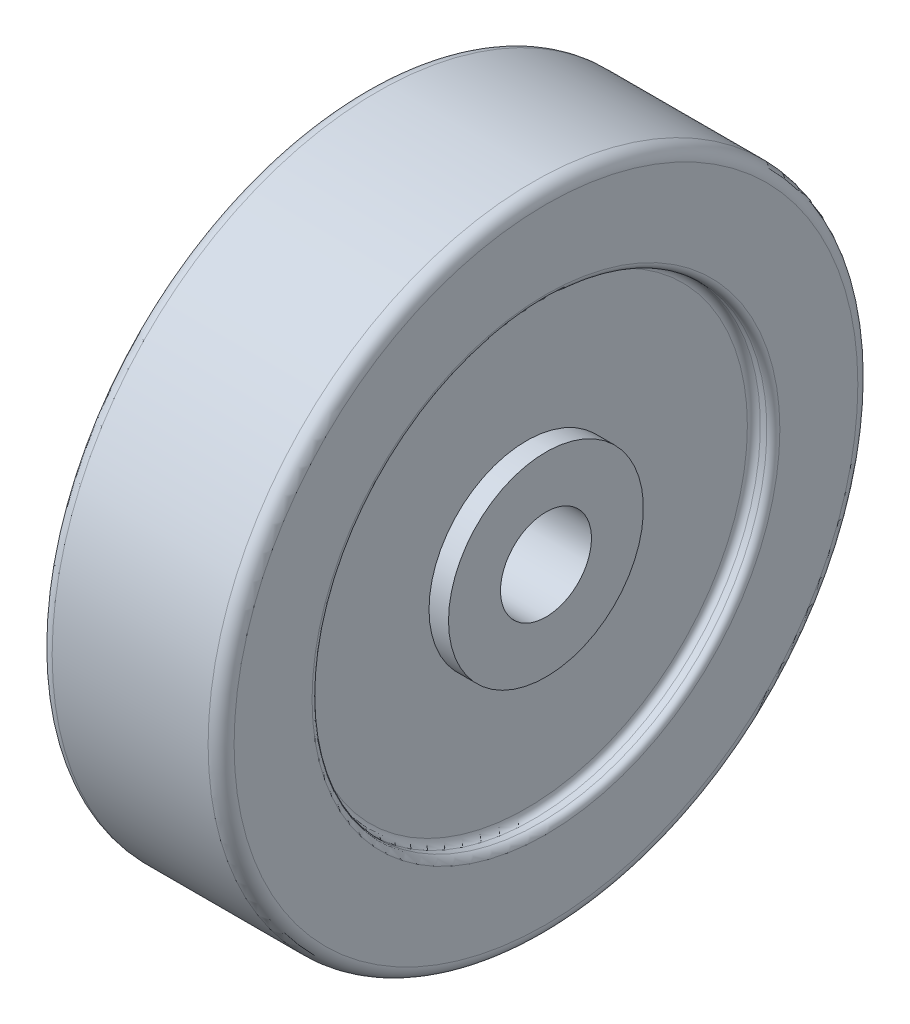
SolidWorks part; units mm, degrees
ref_plane "Alzado" through (0, 0, 0) normal (0, 0, 1) x (1, 0, 0)
ref_plane "Planta" through (0, 0, 0) normal (0, 1, 0) x (1, 0, 0)
ref_plane "Vista lateral" through (0, 0, 0) normal (1, 0, 0) x (0, 0, -1)
sketch "Croquis1" plane through (0, 0, 0) normal (0, 0, 1) x (1, 0, 0)
  line L0 (-1.552, 0) -> (2.7075, 0) construction
  line L1 (0, 7) -> (28, 7)
  line L2 (28, 7) -> (28, 15)
  line L3 (28, 15) -> (25, 15)
  line L4 (25, 15) -> (25, 35)
  line L5 (25, 35) -> (28, 35)
  line L6 (28, 35) -> (28, 50)
  line L7 (28, 50) -> (0, 50)
  line L8 (0, 50) -> (0, 35)
  line L9 (0, 35) -> (3, 35)
  line L10 (3, 35) -> (3, 15)
  line L11 (3, 15) -> (0, 15)
  line L12 (0, 15) -> (0, 7)
  point P5 (14, 7)
  point P17 (14, 50)
  dimension "D1" = 3
  dimension "D2" = 3
  dimension "D3" = 28
  dimension "D4" = 50
  dimension "D5" = 35
  dimension "D6" = 7
  dimension "D7" = 15
revolve "Revolución1" add sketch "Croquis1" angle 360 about L0
fillet "Redondeo1" radius 2 2 edges at (0, 0, 50) (28, 0, 50)
fillet "Redondeo2" radius 1 4 edges at (0, 0, 35) (3, 0, 35) (28, 0, 35) (25, 0, 35)
